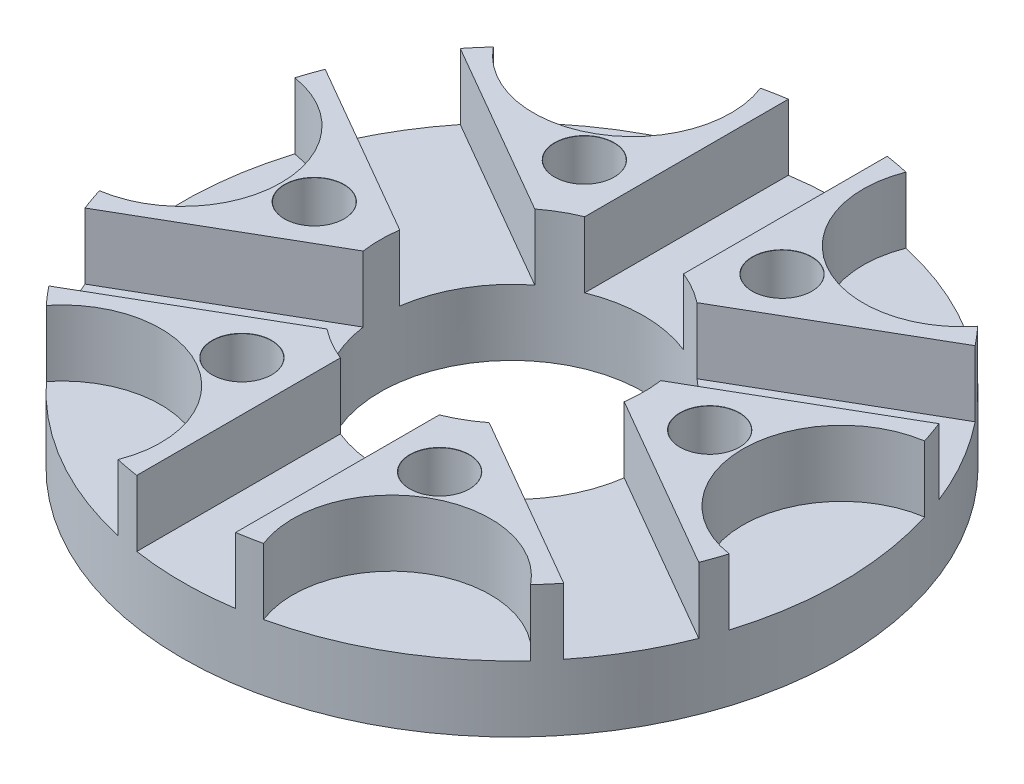
SolidWorks part; units mm, degrees
ref_plane "Front Plane" through (0, 0, 0) normal (0, 0, 1) x (1, 0, 0)
ref_plane "Top Plane" through (0, 0, 0) normal (0, 1, 0) x (1, 0, 0)
ref_plane "Right Plane" through (0, 0, 0) normal (1, 0, 0) x (0, 0, -1)
sketch "Sketch1" plane through (0, 0, 0) normal (0, 1, 0) x (1, 0, 0)
  circle A0 centre (0, 0) radius 50
  dimension "D1" = 100
extrude "Boss-Extrude1" add sketch "Sketch1" along normal mid plane 20
sketch "Sketch2" plane through (0, 10, 0) normal (0, 1, 0) x (1, 0, 0)
  circle A0 centre (0, 0) radius 20
  dimension "D1" = 40
extrude "Cut-Extrude1" cut sketch "Sketch2" against normal through all
sketch "Sketch3" plane through (0, 10, 0) normal (0, 1, 0) x (1, 0, 0)
  line L0 (-7.5, 49.4343) -> (-7.5, 18.5405)
  line L2 (7.5, 49.4343) -> (7.5, 18.5405)
  line L13 (39.0614, 31.2123) -> (12.3065, 15.7654)
  line L14 (0, 0) -> (66.8112, 0) construction
  line L15 (0, 0) -> (0, 75.3403) construction
  line L16 (46.5614, 18.222) -> (19.8065, 2.7751)
  line L17 (46.5614, -18.222) -> (19.8065, -2.7751)
  line L18 (39.0614, -31.2123) -> (12.3065, -15.7654)
  line L19 (7.5, -49.4343) -> (7.5, -18.5405)
  line L20 (-7.5, -49.4343) -> (-7.5, -18.5405)
  line L21 (-39.0614, -31.2123) -> (-12.3065, -15.7654)
  line L22 (-46.5614, -18.222) -> (-19.8065, -2.7751)
  line L23 (-46.5614, 18.222) -> (-19.8065, 2.7751)
  line L24 (-39.0614, 31.2123) -> (-12.3065, 15.7654)
  arc A14 (-7.5, 18.5405) -> (7.5, 18.5405) centre (0, 0) cw
  arc A16 (-7.5, 49.4343) -> (7.5, 49.4343) centre (0, 0) cw
  circle A17 centre (0, 0) radius 20 construction
  circle A18 centre (0, 0) radius 50 construction
  arc A19 (12.3065, 15.7654) -> (19.8065, 2.7751) centre (0, 0) cw
  arc A20 (39.0614, 31.2123) -> (46.5614, 18.222) centre (0, 0) cw
  arc A21 (19.8065, -2.7751) -> (12.3065, -15.7654) centre (0, 0) cw
  arc A22 (46.5614, -18.222) -> (39.0614, -31.2123) centre (0, 0) cw
  arc A23 (7.5, -18.5405) -> (-7.5, -18.5405) centre (0, 0) cw
  arc A24 (7.5, -49.4343) -> (-7.5, -49.4343) centre (0, 0) cw
  arc A25 (-12.3065, -15.7654) -> (-19.8065, -2.7751) centre (0, 0) cw
  arc A26 (-39.0614, -31.2123) -> (-46.5614, -18.222) centre (0, 0) cw
  arc A27 (-19.8065, 2.7751) -> (-12.3065, 15.7654) centre (0, 0) cw
  arc A28 (-46.5614, 18.222) -> (-39.0614, 31.2123) centre (0, 0) cw
  point P31 (0, 0)
  dimension "D2" = 6
  dimension "D1" = 15
extrude "Cut-Extrude2" cut sketch "Sketch3" against normal blind 10
sketch "Sketch4" plane through (0, 10, 0) normal (0, 1, 0) x (1, 0, 0)
  arc A0 (11, 48.775) -> (36.6964, 33.9613) centre (24.9719, 43.3175) ccw
  arc A1 (39.0614, 31.2123) -> (7.5, 49.4343) centre (0, 0) ccw construction
  arc A3 (36.6964, 33.9613) -> (11, 48.775) centre (0, 0) ccw
  dimension "D1" = 15
  dimension "D2" = 3.5
extrude "Cut-Extrude3" cut sketch "Sketch4" against normal blind 10
hole_wizard "Tap Drill for M10x1.0 Tap1" positions "Sketch5" profile "Sketch6" hole size "M10x1.0" standard "ISO"
sketch "Sketch5" plane through (0, 10, 0) normal (0, 1, 0) x (1, 0, 0)
  circle A0 centre (0, 0) radius 30 construction
  point P0 (30, 0)
  point P8 (0, 0)
  point P9 (30, 0)
  dimension "D1" = 60
sketch "Sketch6" plane through (30, 10, 0) normal (1, 0, 0) x (0, 0, 1)
  line L0 (0, 0) -> (0, 72.7039)
  line L1 (0, 72.7039) -> (4.5, 70)
  line L2 (4.5, 70) -> (4.5, 0.025)
  line L3 (4.5, 0.025) -> (4.525, 0)
  line L5 (4.525, 0) -> (0, 0)
  line L6 (-4.5, 0.025) -> (-4.525, 0) construction
  line L10 (0, 72.7039) -> (-4.5, 70) construction
  line L11 (0, -6.35) -> (0, 107.95) construction
  dimension "Hole Dia." = 9
  dimension "Hole Depth" = 70
  dimension "Near C'Sink Dia." = 9.05
  dimension "Near C'Sink Angle" = 90
  dimension "Drill Angle" = 118
pattern_circular "CirPattern1" count 6 over 360 about axis through (0, 0, 0) along (0, 1, 0) of "Tap Drill for M10x1.0 Tap1"
pattern_circular "CirPattern2" count 6 over 360 about axis through (0, 0, 0) along (0, 1, 0) of "Cut-Extrude3"
